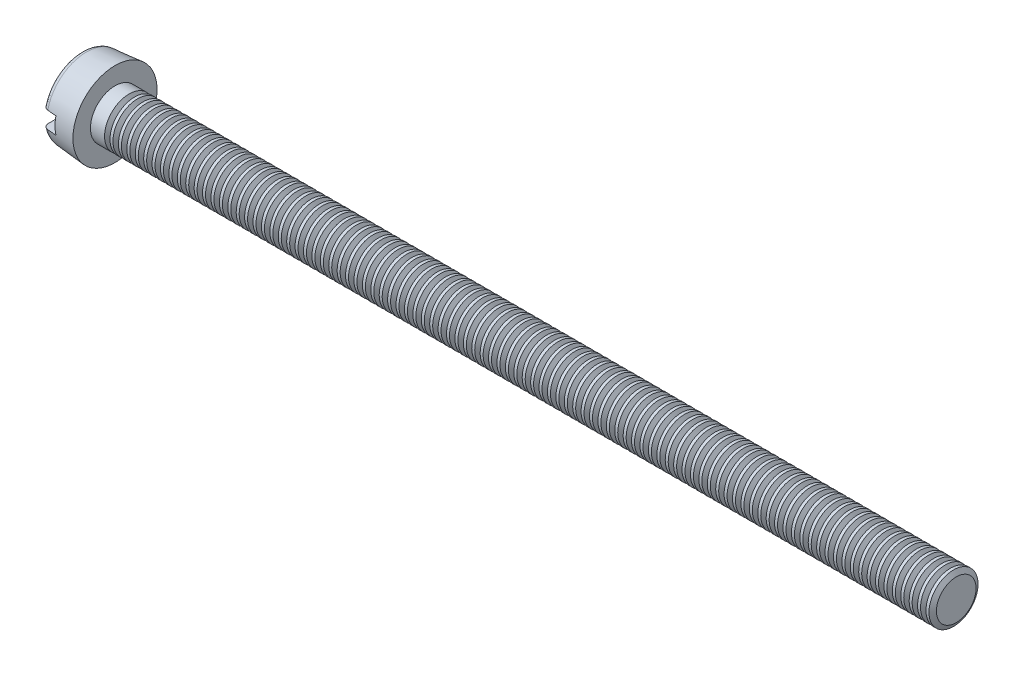
SolidWorks part; units mm, degrees
ref_plane "Front Plane" through (0, 0, 0) normal (0, 0, 1) x (1, 0, 0)
ref_plane "Top Plane" through (0, 0, 0) normal (0, 1, 0) x (1, 0, 0)
ref_plane "Right Plane" through (0, 0, 0) normal (1, 0, 0) x (0, 0, -1)
sketch "BodySke" plane through (0, 0, 0) normal (0, 0, 1) x (1, 0, 0)
  line L0 (0, 0) -> (111.3824, 0) construction
  line L1 (0, 0) -> (0, 2.79)
  line L2 (0, 2.79) -> (2.4, 3)
  line L3 (2.4, 3) -> (2.4, 1.75)
  line L4 (2.4, 1.75) -> (62.4, 1.75)
  line L5 (62.4, 1.75) -> (62.4, 0)
  line L6 (3, 8.824) -> (3, -5.8939) construction
  line L7 (0, 0) -> (62.4, 0)
  line L8 (3.6, 5.574) -> (3.6, -8.208) construction
  point P10 (62.4, 1.4145)
  dimension "Thread_minor" = 2.829
  dimension "Diameter" = 3.5
  dimension "Head_dia" = 6
  dimension "Head_height" = 2.4
  dimension "Head_side_angle" = 5
  dimension "Length" = 60
  dimension "Advance" = 0.6
  dimension "Thread_runout" = 1.2
revolve "BaseBody" add sketch "BodySke" angle 360 about L0
cosmetic thread "ThreadCosmetic" [suppressed] parameters "Thread_minor"=2.829
fillet "Fillet1" radius 0.4 1 edges at (0, 0, 2.79)
sketch "SlotSke" plane through (0, 0, 0) normal (-1, 0, 0) x (0, 0, 1)
  line L1 (-3, 0.6) -> (3, 0.6)
  line L2 (-3, 0.6) -> (-3, -0.6)
  line L3 (-3, -0.6) -> (3, -0.6)
  line L4 (3, 0.6) -> (3, -0.6)
  dimension "D1" = 6
  dimension "D2" = 3
  dimension "Slot_width" = 1.2
  dimension "D3" = 0.6
extrude "Slot" cut sketch "SlotSke" against normal blind 1
sketch "ThdSchSke" plane through (0, 0, 0) normal (0, 0, 1) x (1, 0, 0)
  line L0 (0, 0) -> (55.1256, 0) construction
  line L1 (0, 0) -> (111.3824, 0) construction
  line L2 (62.2063, 1.75) -> (62.2063, 2.1374)
  line L3 (62.2063, 2.1374) -> (62.5937, 2.1374)
  line L4 (62.5937, 2.1374) -> (62.5937, 1.75)
  line L5 (62.5937, 1.75) -> (62.4, 1.4145)
  line L6 (62.4, 1.4145) -> (62.2063, 1.75)
  line L7 (2.4, 1.75) -> (62.4, 1.75) construction
  line L13 (62.4, 1.75) -> (62.4, 0) construction
revolve "ThreadSchematic" cut sketch "ThdSchSke" angle 360 about L0
pattern_linear "ThdSchPat" count 99 spacing 0.6 along (-1, 0, 0) of "ThreadSchematic"
equation "\"Thread_minor@ThreadCosmetic\" = \"Thread_minor@BodySke\""
equation "\"D1@SlotSke\" = \"Head_dia@BodySke\""
equation "\"D2@SlotSke\" = \"D1@SlotSke\" / 2"
equation "\"D3@SlotSke\" = \"Slot_width@SlotSke\" / 2"
equation "\"Advance@ThdSchPat\" = \"Advance@BodySke\""
equation "\"D1@ThdSchPat\" =  int(  ( \"Length@BodySke\" - \"Thread_runout@BodySke\" )  / \"Advance@ThdSchPat\" )  + 1"
